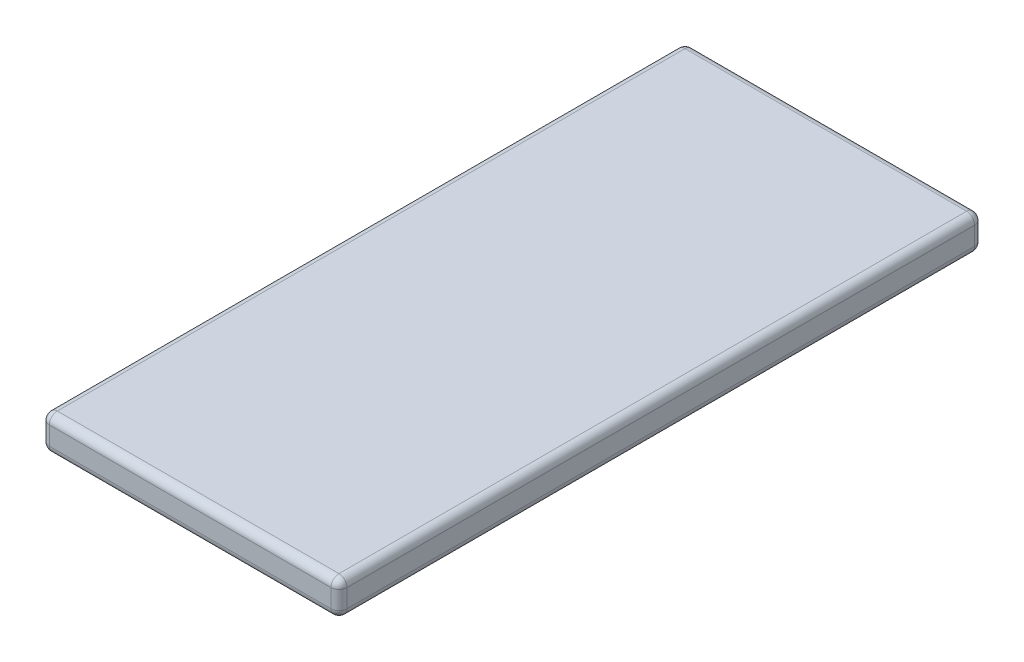
SolidWorks part; units mm, degrees
material "ABS PC"
ref_plane "Front Plane" through (0, 0, 0) normal (0, 0, 1) x (1, 0, 0)
ref_plane "Top Plane" through (0, 0, 0) normal (0, 1, 0) x (1, 0, 0)
ref_plane "Right Plane" through (0, 0, 0) normal (1, 0, 0) x (0, 0, -1)
sketch "Sketch1" plane through (0, 0, 0) normal (0, 1, 0) x (1, 0, 0)
  line L1 (-37, 80) -> (37, 80)
  line L2 (-37, 80) -> (-37, -80)
  line L3 (-37, -80) -> (37, -80)
  line L4 (37, 80) -> (37, -80)
  line L5 (-37, 80) -> (37, -80) construction
  line L6 (-37, -80) -> (37, 80) construction
  point P0 (0, 0)
  dimension "D1" = 74
  dimension "D2" = 160
extrude "Boss-Extrude1" add sketch "Sketch1" along normal blind 8.56
fillet "Fillet1" radius 2 12 edges at (0, 0, -80) (-37, 0, 0) (0, 0, 80) (37, 0, 0) (0, 8.56, 80) (-37, 8.56, 0) (0, 8.56, -80) (37, 8.56, 0) (-37, 4.28, 80) (37, 4.28, 80) (37, 4.28, -80) (-37, 4.28, -80)
